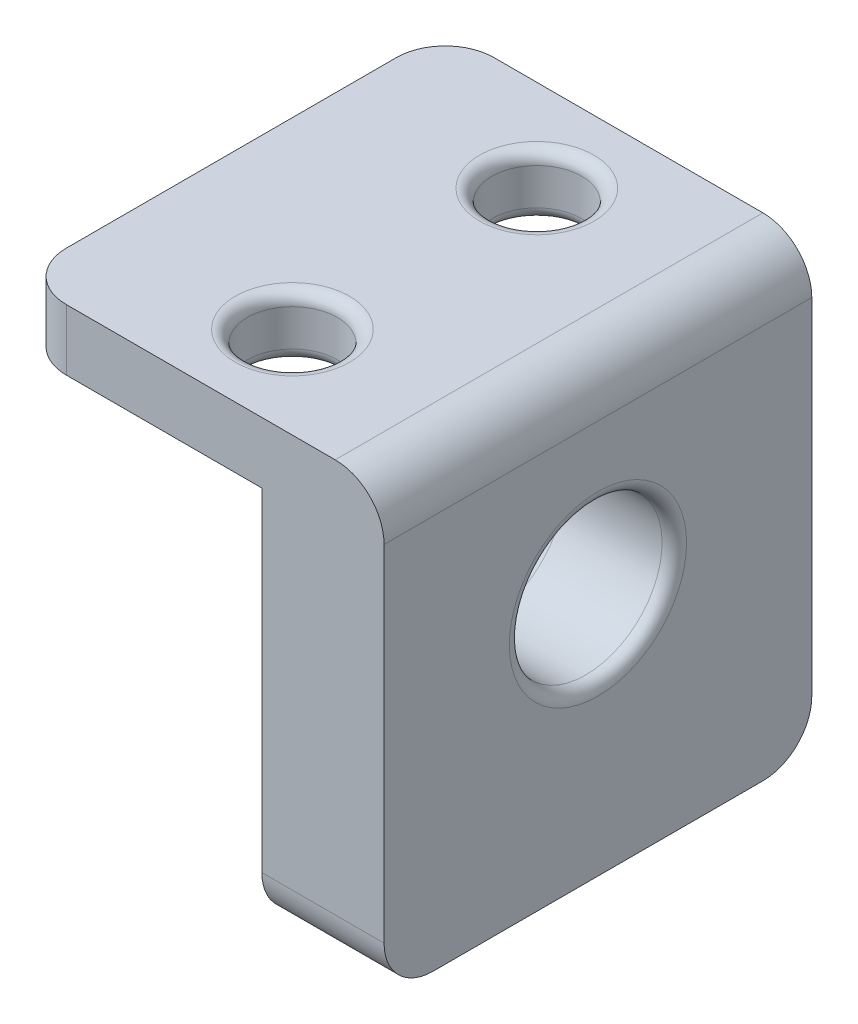
SolidWorks part; units mm, degrees
ref_plane "Front Plane" through (0, 0, 0) normal (0, 0, 1) x (1, 0, 0)
ref_plane "Top Plane" through (0, 0, 0) normal (0, 1, 0) x (1, 0, 0)
ref_plane "Right Plane" through (0, 0, 0) normal (1, 0, 0) x (0, 0, -1)
sketch "Sketch1" plane through (0, 0, 0) normal (0, 0, 1) x (1, 0, 0)
  line L0 (0, 0) -> (-12.7, 0) construction
  line L1 (-12.7, 0) -> (-12.7, 6.35) construction
  line L2 (-12.7, 6.35) -> (0, 6.35) construction
  line L3 (0, 6.35) -> (0, 19.05) construction
  line L4 (0, 19.05) -> (6.35, 19.05) construction
  line L5 (6.35, 19.05) -> (6.35, -25.4) construction
  line L6 (6.35, -25.4) -> (0, -25.4) construction
  line L7 (0, -25.4) -> (0, 0) construction
  line L8 (3.175, 19.05) -> (3.175, -25.4) construction
  line L10 (0, -2.3812) -> (0, -5.5562)
  line L11 (0, -5.5562) -> (12.7, -5.5562)
  line L12 (12.7, -5.5562) -> (12.7, -25.4)
  line L13 (12.7, -25.4) -> (19.05, -25.4)
  line L14 (19.05, -25.4) -> (19.05, -2.3812)
  line L15 (19.05, -2.3812) -> (0, -2.3812)
  line L16 (15.875, -25.4) -> (15.875, -2.3812) construction
  point P10 (3.175, -12.7)
  point P11 (3.175, 12.7)
  point P14 (15.875, -12.7)
  point P22 (0, 0)
  point P23 (0, 0)
  dimension "D1" = 12.7
  dimension "D2" = 6.35
  dimension "D3" = 6.35
  dimension "D4" = 44.45
  dimension "D5" = 25.4
  dimension "D6" = 6.35
  dimension "D7" = 25.4
  dimension "D8" = 2.3813
  dimension "D9" = 12.7
  dimension "D10" = 6.35
  dimension "D11" = 12.7
  dimension "D12" = 3.175
extrude "Boss-Extrude1" add sketch "Sketch1" along normal mid plane 22.225
sketch "Sketch2" plane through (19.05, 0, 0) normal (1, 0, 0) x (0, 0, -1)
  line L0 (0, -2.3812) -> (0, -25.4) construction
  line L1 (-11.1125, -2.3812) -> (11.1125, -2.3812) construction
  line L2 (-11.1125, -25.4) -> (11.1125, -25.4) construction
  circle A0 centre (0, -12.7) radius 3.9688
  point P8 (0, 0)
  point P9 (0, 0)
  point P10 (0, 0)
  point P11 (0, 0)
  point P12 (0, 0)
  point P13 (0, 0)
  point P14 (0, 0)
  dimension "D1" = 7.9375
extrude "Cut-Extrude1" cut sketch "Sketch2" against normal blind 22.225
fillet "Fillet1" radius 0.635 2 edges at (12.7, -8.7313, 0) (19.05, -12.7, -3.9688)
fillet "Fillet2" radius 2.54 5 edges at (19.05, -2.3812, 0) (0, -3.9688, 11.1125) (0, -3.9688, -11.1125) (15.875, -25.4, -11.1125) (15.875, -25.4, 11.1125)
sketch "Sketch3" plane through (0, -2.3812, 0) normal (0, 1, 0) x (1, 0, 0)
  line L0 (9.525, 11.1125) -> (9.525, -11.1125) construction
  line L1 (16.51, 11.1125) -> (2.54, 11.1125) construction
  line L2 (16.51, -11.1125) -> (2.54, -11.1125) construction
  circle A0 centre (9.525, 6.35) radius 2.3368
  circle A1 centre (9.525, -6.35) radius 2.3368
  point P10 (0, 0)
  point P11 (0, 0)
  dimension "D1" = 4.6736
  dimension "D2" = 12.7
  dimension "D3" = 4.7625
  dimension "D4" = 4.7625
extrude "Cut-Extrude2" cut sketch "Sketch3" against normal blind 22.225
fillet "Fillet3" radius 0.635 4 edges at (9.525, -5.5562, -4.0132) (7.1882, -2.3812, -6.35) (9.525, -5.5562, 8.6868) (7.1882, -2.3812, 6.35)
